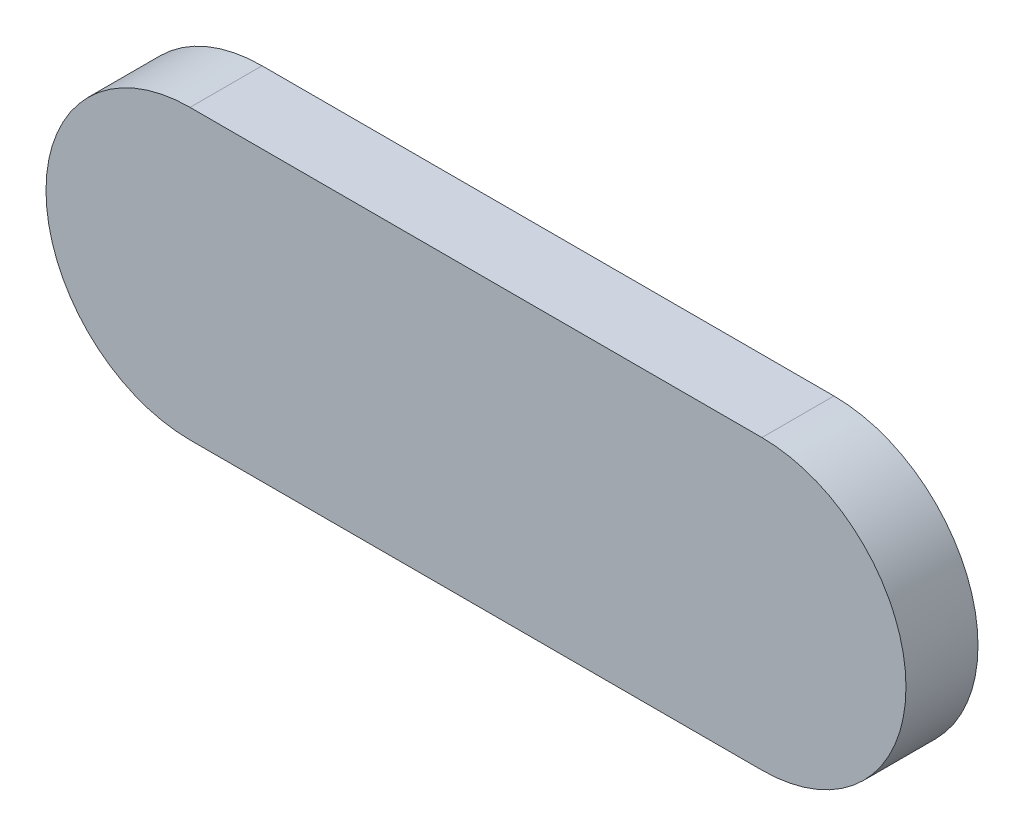
SolidWorks part; units mm, degrees
ref_plane "Спереди" through (0, 0, 0) normal (0, 0, 1) x (1, 0, 0)
ref_plane "Сверху" through (0, 0, 0) normal (0, 1, 0) x (1, 0, 0)
ref_plane "Справа" through (0, 0, 0) normal (1, 0, 0) x (0, 0, -1)
other "Configuration Table"
sketch "Эскиз1" plane through (0, 0, 0) normal (0, 0, 1) x (1, 0, 0)
  line L0 (-19.85, 0) -> (19.85, 0) construction
  line L8 (-19.85, 10) -> (19.85, 10)
  line L9 (-19.85, -10) -> (19.85, -10)
  arc A3 (-19.85, 10) -> (-19.85, -10) centre (-19.85, 0) ccw
  arc A4 (19.85, -10) -> (19.85, 10) centre (19.85, 0) ccw
  point P2 (0, 0)
  point P4 (0, 0)
  dimension "D1" = 20
  dimension "D2" = 39.7
extrude "Бобышка-Вытянуть2" add sketch "Эскиз1" along normal blind 5 contours A3 L9 A4 L8
